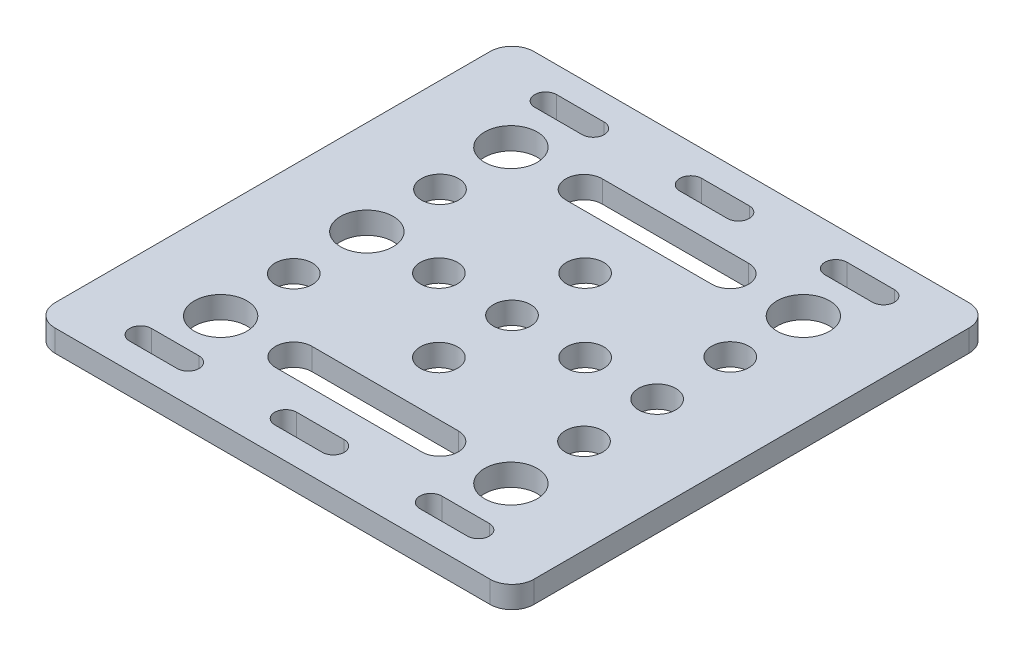
SolidWorks part; units mm, degrees
ref_plane "Front Plane" through (0, 0, 0) normal (0, 0, 1) x (1, 0, 0)
ref_plane "Top Plane" through (0, 0, 0) normal (0, 1, 0) x (1, 0, 0)
ref_plane "Right Plane" through (0, 0, 0) normal (1, 0, 0) x (0, 0, -1)
sketch "Sketch1" plane through (0, 0, 0) normal (0, 1, 0) x (1, 0, 0)
  line L0 (-32.75, 0) -> (32.75, 0) construction
  line L1 (-29.75, 32.75) -> (29.75, 32.75)
  line L2 (-32.75, 29.75) -> (-32.75, -29.75)
  line L3 (-29.75, -32.75) -> (29.75, -32.75)
  line L4 (32.75, 29.75) -> (32.75, -29.75)
  line L5 (-32.75, 32.75) -> (32.75, -32.75) construction
  line L6 (-32.75, -32.75) -> (32.75, 32.75) construction
  line L7 (0, 32.75) -> (0, -32.75) construction
  line L8 (19.85, 10) -> (19.85, 32.75) construction
  line L9 (-3.25, 29.2) -> (3.25, 29.2)
  line L11 (-3.25, 26.2) -> (3.25, 26.2)
  line L13 (-3.25, 29.2) -> (3.25, 26.2) construction
  line L14 (-3.25, 26.2) -> (3.25, 29.2) construction
  line L15 (-16.6, 29.2) -> (-23.1, 26.2) construction
  line L16 (16.6, 29.2) -> (23.1, 29.2)
  line L18 (16.6, 26.2) -> (23.1, 26.2)
  line L20 (16.6, 29.2) -> (23.1, 26.2) construction
  line L21 (16.6, 26.2) -> (23.1, 29.2) construction
  line L22 (-16.6, 26.2) -> (-23.1, 26.2)
  line L23 (-16.6, 29.2) -> (-23.1, 29.2)
  line L24 (-16.6, 26.2) -> (-23.1, 29.2) construction
  line L25 (-16.6, -26.2) -> (-23.1, -29.2) construction
  line L26 (16.6, -26.2) -> (23.1, -29.2) construction
  line L27 (16.6, -29.2) -> (23.1, -26.2) construction
  line L28 (-16.6, -29.2) -> (-23.1, -26.2) construction
  line L29 (-3.25, -26.2) -> (3.25, -29.2) construction
  line L30 (-3.25, -29.2) -> (3.25, -26.2) construction
  line L31 (-16.6, -29.2) -> (-23.1, -29.2)
  line L32 (-16.6, -26.2) -> (-23.1, -26.2)
  line L33 (16.6, -26.2) -> (23.1, -26.2)
  line L34 (16.6, -29.2) -> (23.1, -29.2)
  line L35 (-3.25, -26.2) -> (3.25, -26.2)
  line L36 (-3.25, -29.2) -> (3.25, -29.2)
  line L37 (-10, -17.35) -> (10, -17.35)
  line L38 (-10, 22.35) -> (10, 22.35)
  line L40 (-10, 17.35) -> (10, 17.35)
  line L42 (-10, 22.35) -> (10, 17.35) construction
  line L43 (-10, 17.35) -> (10, 22.35) construction
  line L44 (-10, -22.35) -> (10, -17.35) construction
  line L45 (-10, -17.35) -> (10, -22.35) construction
  line L46 (-10, -22.35) -> (10, -22.35)
  arc A0 (-32.75, 29.75) -> (-29.75, 32.75) centre (-29.75, 29.75) cw
  arc A1 (-29.75, -32.75) -> (-32.75, -29.75) centre (-29.75, -29.75) cw
  arc A2 (32.75, -29.75) -> (29.75, -32.75) centre (29.75, -29.75) cw
  arc A3 (29.75, 32.75) -> (32.75, 29.75) centre (29.75, 29.75) cw
  circle A4 centre (-20, 19.85) radius 3.6
  circle A5 centre (-19.85, 0) radius 3.6
  circle A6 centre (-19.85, -20) radius 3.6
  circle A7 centre (-19.85, 10) radius 2.55
  circle A8 centre (-19.85, -10) radius 2.55
  circle A9 centre (19.85, -20) radius 3.6
  circle A10 centre (20, 19.85) radius 3.6
  circle A11 centre (19.85, 10) radius 2.55
  circle A12 centre (19.85, -10) radius 2.55
  circle A13 centre (19.85, 0) radius 2.55
  circle A14 centre (0, 0) radius 2.55
  circle A15 centre (10, 0) radius 2.55
  circle A16 centre (0, 10) radius 2.55
  circle A17 centre (-10, 0) radius 2.55
  circle A18 centre (0, -10) radius 2.55
  arc A19 (3.25, 26.2) -> (3.25, 29.2) centre (3.25, 27.7) ccw
  arc A20 (-3.25, 26.2) -> (-3.25, 29.2) centre (-3.25, 27.7) cw
  arc A21 (23.1, 26.2) -> (23.1, 29.2) centre (23.1, 27.7) ccw
  arc A22 (16.6, 26.2) -> (16.6, 29.2) centre (16.6, 27.7) cw
  arc A23 (-16.6, 26.2) -> (-16.6, 29.2) centre (-16.6, 27.7) ccw
  arc A24 (-23.1, 26.2) -> (-23.1, 29.2) centre (-23.1, 27.7) cw
  arc A25 (-23.1, -26.2) -> (-23.1, -29.2) centre (-23.1, -27.7) ccw
  arc A26 (-16.6, -26.2) -> (-16.6, -29.2) centre (-16.6, -27.7) cw
  arc A27 (16.6, -26.2) -> (16.6, -29.2) centre (16.6, -27.7) ccw
  arc A28 (23.1, -26.2) -> (23.1, -29.2) centre (23.1, -27.7) cw
  arc A29 (-3.25, -26.2) -> (-3.25, -29.2) centre (-3.25, -27.7) ccw
  arc A30 (3.25, -26.2) -> (3.25, -29.2) centre (3.25, -27.7) cw
  arc A31 (10, 17.35) -> (10, 22.35) centre (10, 19.85) ccw
  arc A32 (-10, 17.35) -> (-10, 22.35) centre (-10, 19.85) cw
  arc A33 (10, -17.35) -> (10, -22.35) centre (10, -19.85) cw
  arc A34 (-10, -17.35) -> (-10, -22.35) centre (-10, -19.85) ccw
  point P0 (0, 0)
  point P54 (0, 27.7)
  point P59 (19.85, 27.7)
  point P91 (19.85, -27.7)
  point P92 (0, -27.7)
  point P93 (0, 19.85)
  dimension "D3" = 3
  dimension "D4" = 3
  dimension "D5" = 3
  dimension "D6" = 3
  dimension "D9" = 7.2
  dimension "D12" = 7.2
  dimension "D13" = 7.2
  dimension "D16" = 5.1
  dimension "D19" = 5.1
  dimension "D21" = 5.1
  dimension "D22" = 5.1
  dimension "D24" = 6.5
  dimension "D25" = 1.5
  dimension "D29" = 1.5
  dimension "D32" = 2.5
  dimension "D35" = 20
  dimension "D1" = 65.5
  dimension "D2" = 65.5
  dimension "D7" = 12.75
  dimension "D8" = 12.9
  dimension "D10" = 12.9
  dimension "D11" = 32.75
  dimension "D14" = 52.75
  dimension "D15" = 12.9
  dimension "D17" = 12.9
  dimension "D18" = 22.75
  dimension "D20" = 12.9
  dimension "D23" = 42.75
  dimension "D26" = 5.05
  dimension "D27" = 3
  dimension "D28" = 6.5
  dimension "D30" = 3
  dimension "D31" = 5.05
  dimension "D33" = 12.9
  dimension "D34" = 5
extrude "Boss-Extrude1" add sketch "Sketch1" along normal blind 3
